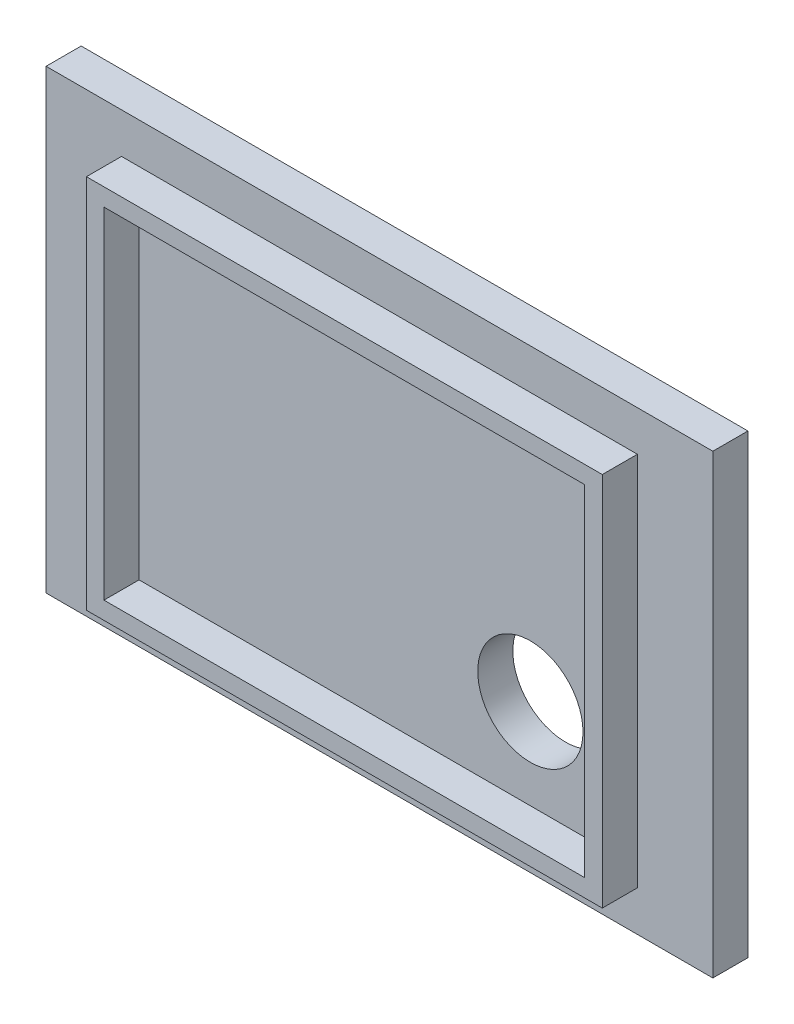
SolidWorks part; units mm, degrees
ref_plane "Front Plane" through (0, 0, 0) normal (0, 0, 1) x (1, 0, 0)
ref_plane "Top Plane" through (0, 0, 0) normal (0, 1, 0) x (1, 0, 0)
ref_plane "Right Plane" through (0, 0, 0) normal (1, 0, 0) x (0, 0, -1)
sketch "Sketch1" plane through (0, 0, 0) normal (0, 0, 1) x (1, 0, 0)
  line L5 (-15, -11) -> (15, -11) construction
  line L6 (-15, -11) -> (-15, 11) construction
  line L7 (-15, 11) -> (15, 11) construction
  line L8 (15, -11) -> (15, 11) construction
  line L9 (-15, -11) -> (15, 11)
  line L10 (-15, 11) -> (15, -11)
  line L11 (19, -13) -> (-19, -13)
  line L12 (19, -13) -> (19, 13)
  line L13 (19, 13) -> (-19, 13)
  line L14 (-19, -13) -> (-19, 13)
  line L15 (19, -13) -> (-19, 13) construction
  line L16 (19, 13) -> (-19, -13) construction
  point P0 (0, 0)
  point P5 (0, 0)
  dimension "D1" = 22
  dimension "D2" = 30
  dimension "D3" = 2
  dimension "D4" = 4
extrude "Boss-Extrude1" add sketch "Sketch1" along normal blind 2
sketch "Sketch4" plane through (0, 0, 2) normal (0, 0, 1) x (1, 0, 0)
  line L0 (19, -13) -> (19, 13) construction
  line L1 (-14.7, -10.7) -> (14.7, -10.7)
  line L2 (-14.7, -10.7) -> (-14.7, 10.7)
  line L3 (-14.7, 10.7) -> (14.7, 10.7)
  line L4 (14.7, -10.7) -> (14.7, 10.7)
  line L5 (-14.7, -10.7) -> (14.7, 10.7) construction
  line L6 (-14.7, 10.7) -> (14.7, -10.7) construction
  line L7 (19, -13) -> (-19, -13) construction
  line L8 (-13.7, 9.7) -> (13.7, 9.7)
  line L9 (13.7, -9.7) -> (13.7, 9.7)
  line L10 (-13.7, -9.7) -> (13.7, -9.7)
  line L11 (-13.7, -9.7) -> (-13.7, 9.7)
  point P0 (0, 0)
  dimension "D1" = 4.3
  dimension "D2" = 2.3
  dimension "D3" = 1
extrude "Boss-Extrude2" add sketch "Sketch4" along normal blind 2
sketch "Sketch5" plane through (0, 0, 2) normal (0, 0, 1) x (1, 0, 0)
  circle A0 centre (8.6008, -4.557) radius 3
extrude "Cut-Extrude1" cut sketch "Sketch5" against normal blind 2
